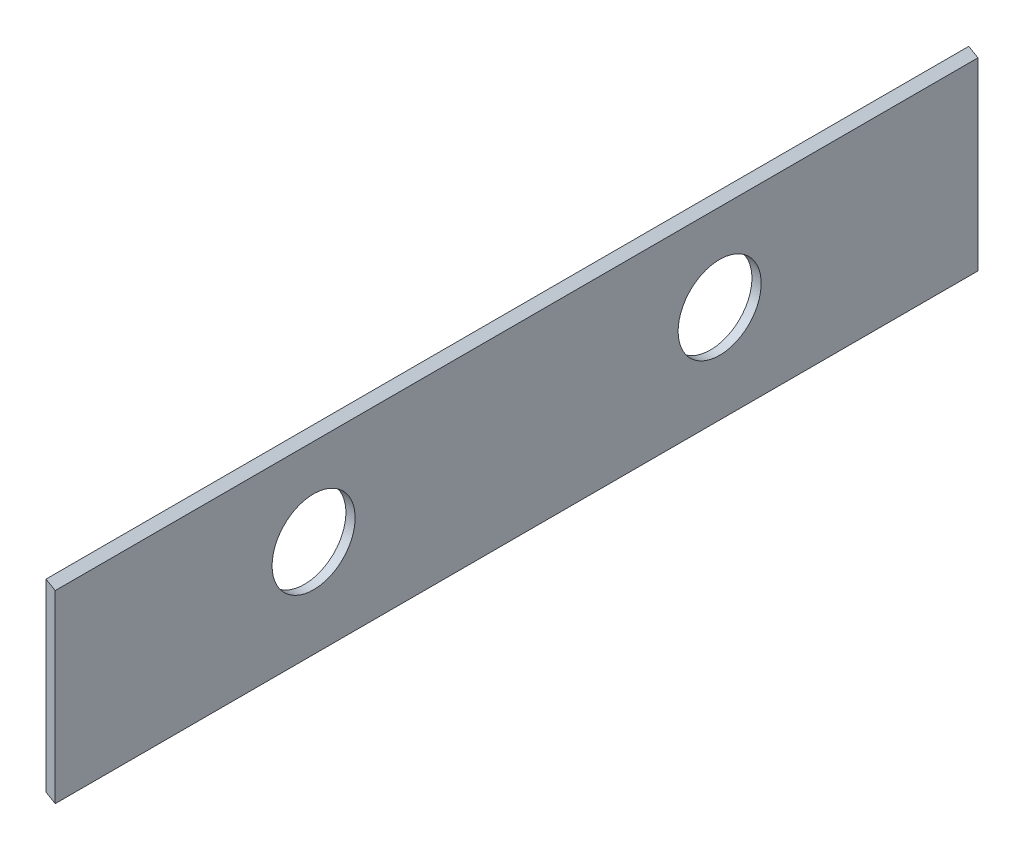
SolidWorks part; units mm, degrees
ref_plane "Alzado" through (0, 0, 0) normal (0, 0, 1) x (1, 0, 0)
ref_plane "Planta" through (0, 0, 0) normal (0, 1, 0) x (1, 0, 0)
ref_plane "Vista lateral" through (0, 0, 0) normal (1, 0, 0) x (0, 0, -1)
sketch "Croquis3" plane through (0, 0, 0) normal (0, 0, 1) x (1, 0, 0)
  line L4 (0, 0) -> (0, 20)
  line L5 (0, 20) -> (-1, 20.5774)
  line L6 (-1, 20.5774) -> (-1, 0.5774)
  line L7 (-1, 0.5774) -> (0, 0)
  line L8 (0, 0) -> (-7.846, 0) construction
  dimension "D1" = 20
  dimension "D2" = 30
  dimension "D3" = 1
extrude "Saliente-Extruir2" add sketch "Croquis3" along normal mid plane 100
hole_wizard "Taladro de margen para M82" positions "Croquis3D2" profile "Croquis4" hole size "M8" standard "Ansi Metric"
sketch3d "Croquis3D2"
  line L0 (-1, 20.5774, -50) -> (-1, 0.5774, -50) construction
  line L1 (-1, 20.5774, 0) -> (-1, 0.5774, 0) construction
  line L2 (-1, 20.5774, 50) -> (-1, 20.5774, -50) construction
  line L3 (-1, 0.5774, 50) -> (-1, 0.5774, -50) construction
  point P0 (-1, 10.5774, -22)
  point P2 (-1, 10.5774, 22)
  point P8 (-1, 10.5774, -50)
  dimension "D1" = 22
  dimension "D2" = 22
sketch "Croquis4" plane through (-1, 10.5774, -22) normal (0, 1, 0) x (0, 0, 1)
  line L0 (0, 0) -> (0, 12.7039)
  line L1 (0, 12.7039) -> (4.5, 10)
  line L2 (4.5, 10) -> (4.5, 0)
  line L5 (4.5, 0) -> (0, 0)
  line L10 (0, 12.7039) -> (-4.5, 10) construction
  line L11 (0, -6.35) -> (0, 107.95) construction
  dimension "Diámetro de taladro" = 9
  dimension "Profundidad de taladro" = 10
  dimension "Ángulo de perforador" = 118
